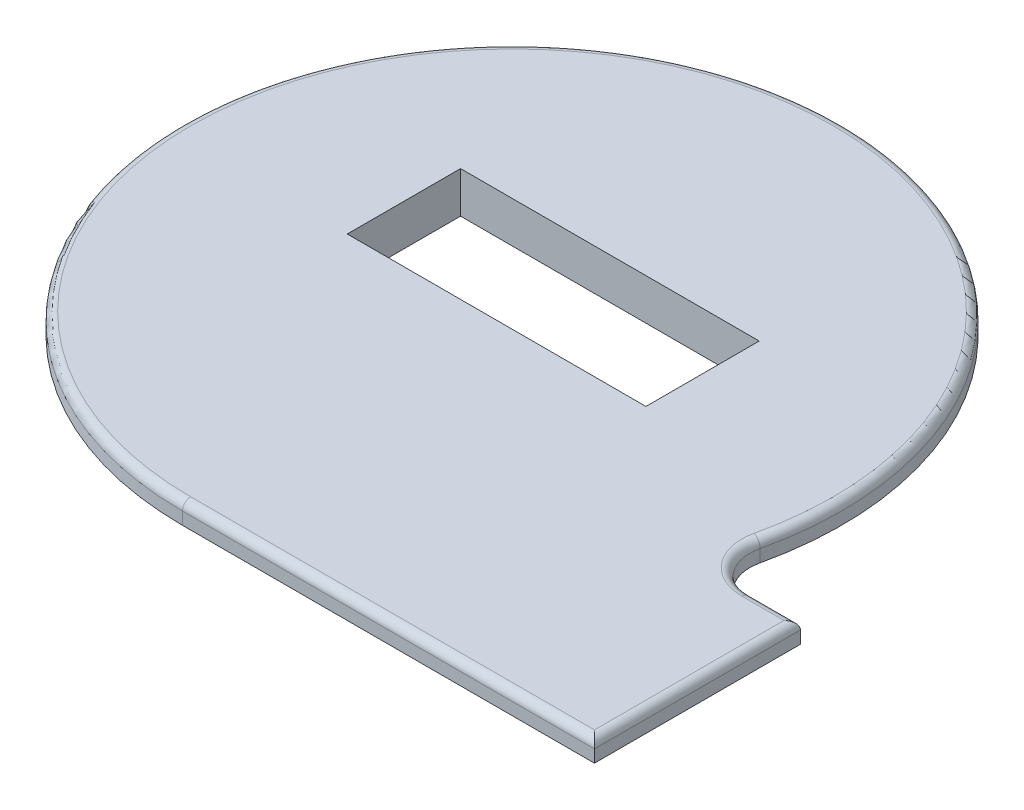
SolidWorks part; units mm, degrees
ref_plane "Front Plane" through (0, 0, 0) normal (0, 0, 1) x (1, 0, 0)
ref_plane "Top Plane" through (0, 0, 0) normal (0, 1, 0) x (1, 0, 0)
ref_plane "Right Plane" through (0, 0, 0) normal (1, 0, 0) x (0, 0, -1)
sketch "Sketch1" plane through (0, 0, 0) normal (0, 1, 0) x (1, 0, 0)
  line L0 (0, -80) -> (100, -80)
  line L1 (100, -80) -> (100, -30)
  line L2 (100, -30) -> (74.162, -30)
  arc A0 (74.162, -30) -> (0, -80) centre (0, 0) ccw
  dimension "D1" = 160
  dimension "D2" = 100
  dimension "D3" = 50
extrude "Boss-Extrude1" add sketch "Sketch1" along normal blind 5
sketch "Sketch2" plane through (0, 0, 0) normal (0, -1, 0) x (1, 0, 0)
  line L0 (0, 74.8) -> (94.8, 74.8)
  line L1 (94.8, 74.8) -> (94.8, 35.2)
  line L2 (94.8, 35.2) -> (66, 35.2)
  line L3 (100, 80) -> (100, 30) construction
  line L5 (100, 30) -> (74.162, 30) construction
  arc A0 (0, 74.8) -> (66, 35.2) centre (0, 0) ccw
  arc A1 (0, 80) -> (74.162, 30) centre (0, 0) ccw construction
  dimension "D1" = 5.2
  dimension "D2" = 5.2
  dimension "D3" = 5.2
extrude "Boss-Extrude2" add sketch "Sketch2" along normal blind 5
sketch "Sketch3" plane through (0, 5, 0) normal (0, 1, 0) x (1, 0, 0)
  line L1 (-36.25, -3.75) -> (36.25, -3.75)
  line L2 (-36.25, -3.75) -> (-36.25, 23.75)
  line L3 (-36.25, 23.75) -> (36.25, 23.75)
  line L4 (36.25, -3.75) -> (36.25, 23.75)
  line L5 (-36.25, -3.75) -> (36.25, 23.75) construction
  line L6 (-36.25, 23.75) -> (36.25, -3.75) construction
  point P0 (0, 10)
  dimension "D1" = 72.5
  dimension "D2" = 27.5
  dimension "D3" = 10
extrude "Cut-Extrude1" cut sketch "Sketch3" against normal through all
sketch "Sketch4" plane through (0, -5, 0) normal (0, -1, 0) x (1, 0, 0)
  line L0 (-37.5, 5.5) -> (37.5, 5.5) construction
  line L1 (37.5, 5.5) -> (37.5, -25.5) construction
  line L2 (37.5, -25.5) -> (-37.5, -25.5) construction
  line L3 (-37.5, -25.5) -> (-37.5, 5.5) construction
  line L4 (0, 0) -> (0, 5.5) construction
  line L5 (-37.5, -25.5) -> (37.5, 5.5) construction
  line L6 (0, -10) -> (0, -23.75) construction
  line L7 (36.25, -23.75) -> (-36.25, -23.75) construction
  line L8 (-36.25, 3.75) -> (36.25, -23.75) construction
  circle A0 centre (-37.5, 5.5) radius 1.5
  circle A1 centre (37.5, 5.5) radius 1.5
  circle A2 centre (37.5, -25.5) radius 1.5
  circle A3 centre (-37.5, -25.5) radius 1.5
  point P15 (0, -10)
  dimension "D1" = 3
  dimension "D2" = 75
  dimension "D3" = 31
extrude "Cut-Extrude2" cut sketch "Sketch4" against normal blind 5
fillet "Fillet2" radius 10 2 edges at (74.162, 2.5, 30) (66, -2.5, 35.2)
fillet "Fillet3" radius 2 5 edges at (93.8748, 5, 30) (79.9323, 5, 26.2361) (-49.8888, 5, -62.5389) (50, 5, 80) (100, 5, 55)
fillet "Fillet1" radius 2 5 edges at (94.8, -5, 55) (47.4, -5, 74.8) (87.8846, -5, 35.2) (-44.3416, -5, -60.24) (72.9157, -5, 31.128)
